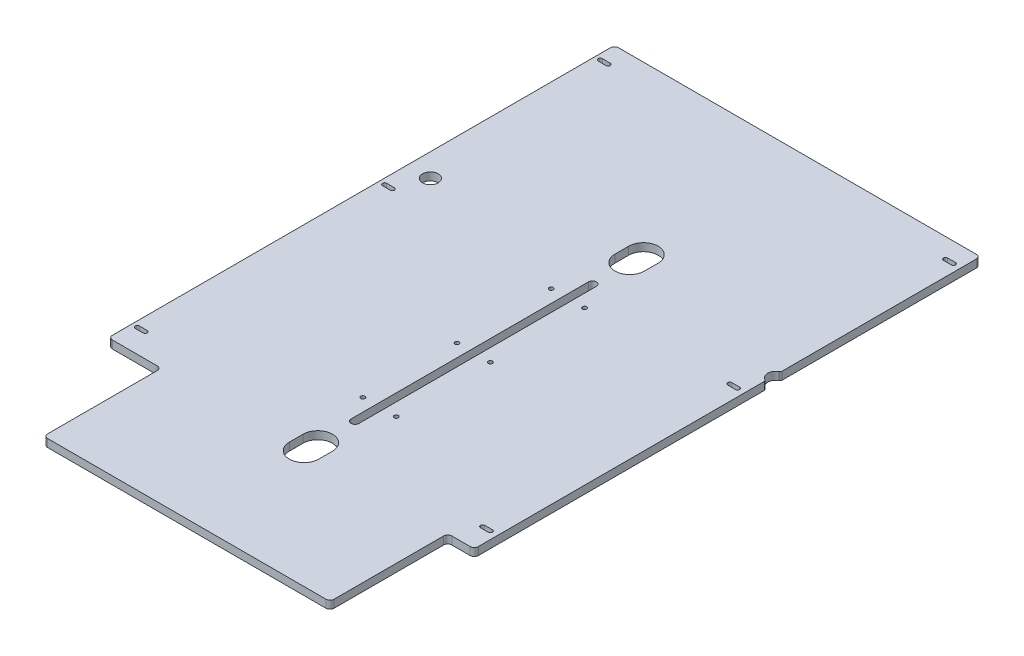
SolidWorks part; units mm, degrees
material "PE High Density"
ref_plane "Front" through (0, 0, 0) normal (0, 0, 1) x (1, 0, 0)
ref_plane "Top" through (0, 0, 0) normal (0, 1, 0) x (1, 0, 0)
ref_plane "Right" through (0, 0, 0) normal (1, 0, 0) x (0, 0, -1)
sketch "Sketch1" plane through (0, 0, 0) normal (0, 1, 0) x (1, 0, 0)
  line L0 (0, 0) -> (96.0438, 0)
  line L1 (96.0438, 0) -> (96.0438, -190.5)
  line L2 (96.0438, -190.5) -> (559.5938, -190.5)
  line L3 (559.5938, -190.5) -> (559.5938, 0)
  line L4 (559.5938, 0) -> (606.425, 0)
  line L5 (606.425, 0) -> (606.425, 819.15)
  line L6 (606.425, 819.15) -> (0, 819.15)
  line L7 (0, 819.15) -> (0, 0)
  line L8 (25.4, 0) -> (25.4, 819.15) construction
  line L9 (19.05, 38.1) -> (31.75, 38.1) construction
  line L10 (19.05, 41.4782) -> (31.75, 41.4782)
  line L11 (19.05, 34.7218) -> (31.75, 34.7218)
  line L12 (19.05, 438.15) -> (31.75, 438.15) construction
  line L13 (19.05, 441.5282) -> (31.75, 441.5282)
  line L14 (19.05, 434.7718) -> (31.75, 434.7718)
  line L15 (31.75, 787.4) -> (19.05, 787.4) construction
  line L16 (31.75, 784.0218) -> (19.05, 784.0218)
  line L17 (31.75, 790.7782) -> (19.05, 790.7782)
  line L18 (303.2125, 819.15) -> (303.2125, -190.5) construction
  line L19 (584.2, 787.4) -> (584.2, 438.15) construction
  line L20 (577.85, 787.4) -> (590.55, 787.4) construction
  line L21 (577.85, 784.0218) -> (590.55, 784.0218)
  line L22 (577.85, 790.7782) -> (590.55, 790.7782)
  line L23 (590.55, 438.15) -> (577.85, 438.15) construction
  line L24 (590.55, 441.5282) -> (577.85, 441.5282)
  line L25 (590.55, 434.7718) -> (577.85, 434.7718)
  line L26 (590.55, 38.1) -> (577.85, 38.1) construction
  line L27 (590.55, 41.4782) -> (577.85, 41.4782)
  line L28 (590.55, 34.7218) -> (577.85, 34.7218)
  line L29 (327.8187, -190.5) -> (327.8187, 819.15) construction
  line L30 (584.2, 438.15) -> (584.2, 38.1) construction
  arc A1 (19.05, 41.4782) -> (19.05, 34.7218) centre (19.05, 38.1) ccw
  arc A2 (31.75, 34.7218) -> (31.75, 41.4782) centre (31.75, 38.1) ccw
  arc A3 (19.05, 441.5282) -> (19.05, 434.7718) centre (19.05, 438.15) ccw
  arc A4 (31.75, 434.7718) -> (31.75, 441.5282) centre (31.75, 438.15) ccw
  arc A5 (31.75, 784.0218) -> (31.75, 790.7782) centre (31.75, 787.4) ccw
  arc A6 (19.05, 790.7782) -> (19.05, 784.0218) centre (19.05, 787.4) ccw
  arc A7 (577.85, 784.0218) -> (577.85, 790.7782) centre (577.85, 787.4) cw
  arc A8 (590.55, 790.7782) -> (590.55, 784.0218) centre (590.55, 787.4) cw
  arc A9 (590.55, 441.5282) -> (590.55, 434.7718) centre (590.55, 438.15) cw
  arc A10 (577.85, 434.7718) -> (577.85, 441.5282) centre (577.85, 438.15) cw
  arc A11 (590.55, 41.4782) -> (590.55, 34.7218) centre (590.55, 38.1) cw
  arc A12 (577.85, 34.7218) -> (577.85, 41.4782) centre (577.85, 38.1) cw
  point P13 (25.4, 38.1)
  point P20 (25.4, 438.15)
  point P27 (25.4, 787.4)
  point P38 (584.2, 787.4)
  point P45 (584.2, 438.15)
  point P52 (584.2, 38.1)
  dimension "D1" = 96.0438
  dimension "D2" = 46.8312
  dimension "D3" = 819.15
  dimension "D4" = 25.4
  dimension "D5" = 6.7564
  dimension "D6" = 38.1
  dimension "D7" = 12.7
  dimension "D8" = 400.05
  dimension "D9" = 349.25
  dimension "D10" = 190.5
  dimension "D11" = 463.55
  dimension "D12" = 22.225
extrude "Boss-Extrude1" add sketch "Sketch1" along normal blind 12.7
fillet "Fillet1" radius 6.604 2 edges at (96.0438, 6.35, 0) (559.5938, 6.35, 0)
fillet "Fillet2" radius 6.604 6 edges at (0, 6.35, -819.15) (606.425, 6.35, -819.15) (606.425, 6.35, 0) (559.5938, 6.35, 190.5) (0, 6.35, 0) (96.0438, 6.35, 190.5)
sketch "Sketch2" plane through (0, 12.7, 0) normal (0, 1, 0) x (1, 0, 0)
  line L1 (606.425, 6.604) -> (606.425, 812.546) construction
  line L3 (577.85, 438.15) -> (590.55, 438.15) construction
  line L4 (606.425, 505.867) -> (606.425, 461.873)
  line L5 (606.425, 483.87) -> (47.625, 483.87) construction
  line L6 (0, 812.546) -> (0, 6.604) construction
  arc A3 (600.075, 494.8685) -> (600.075, 472.8715) centre (606.425, 483.87) ccw
  arc A4 (600.075, 494.8685) -> (606.425, 505.867) centre (593.725, 505.867) ccw
  arc A5 (606.425, 461.873) -> (600.075, 472.8715) centre (593.725, 461.873) ccw
  circle A6 centre (47.625, 483.87) radius 12.7
  dimension "D1" = 25.4
  dimension "D2" = 45.72
  dimension "D3" = 47.625
extrude "Cut-Extrude1" cut sketch "Sketch2" against normal through all
sketch "Sketch4" plane through (0, 0, 0) normal (0, -1, 0) x (1, 0, 0)
  line L0 (0, -812.546) -> (0, -6.604) construction
  line L3 (327.025, -527.05) -> (327.025, -549.275) construction
  line L4 (350.8375, -527.05) -> (350.8375, -549.275)
  line L5 (303.2125, -527.05) -> (303.2125, -549.275)
  line L7 (599.821, -819.15) -> (6.604, -819.15) construction
  line L8 (327.025, 0) -> (327.025, -22.225) construction
  line L9 (350.8375, 0) -> (350.8375, -22.225)
  line L10 (303.2125, 0) -> (303.2125, -22.225)
  circle A0 centre (327.025, -538.1625) radius 28.575 construction
  arc A2 (350.8375, -527.05) -> (303.2125, -527.05) centre (327.025, -527.05) ccw
  arc A3 (303.2125, -549.275) -> (350.8375, -549.275) centre (327.025, -549.275) ccw
  arc A4 (350.8375, 0) -> (303.2125, 0) centre (327.025, 0) ccw
  arc A5 (303.2125, -22.225) -> (350.8375, -22.225) centre (327.025, -22.225) ccw
  point P8 (327.025, -11.1125)
  point P12 (327.025, -538.1625)
  dimension "D2" = 57.15
  dimension "D1" = 327.025
  dimension "D3" = 527.05
  dimension "D4" = 47.625
  dimension "D5" = 22.225
  dimension "D6" = 280.9875
extrude "Cut-Extrude3" cut sketch "Sketch4" against normal through all
sketch "Sketch5" plane through (0, 0, 0) normal (0, -1, 0) x (1, 0, 0)
  line L0 (327.025, -22.225) -> (327.025, -527.05) construction
  line L1 (327.025, -466.725) -> (327.025, -82.55) construction
  line L2 (320.675, -466.725) -> (320.675, -82.55)
  line L3 (333.375, -466.725) -> (333.375, -82.55)
  arc A0 (320.675, -466.725) -> (333.375, -466.725) centre (327.025, -466.725) ccw
  arc A1 (333.375, -82.55) -> (320.675, -82.55) centre (327.025, -82.55) ccw
  point P6 (327.025, -274.6375)
  dimension "D1" = 384.175
  dimension "D2" = 12.7
extrude "Cut-Extrude4" cut sketch "Sketch5" against normal through all
sketch "Sketch6" plane through (0, 0, 0) normal (0, -1, 0) x (1, 0, 0)
  line L0 (327.025, -82.55) -> (327.025, -466.725) construction
  line L1 (327.025, -274.6375) -> (354.0125, -274.6375) construction
  line L2 (354.0125, -122.2375) -> (354.0125, -427.0375) construction
  line L3 (300.0375, -122.2375) -> (300.0375, -427.0375) construction
  circle A0 centre (354.0125, -274.6375) radius 3.3782
  circle A1 centre (354.0125, -427.0375) radius 3.3782
  circle A2 centre (354.0125, -122.2375) radius 3.3782
  circle A3 centre (300.0375, -427.0375) radius 3.3782
  circle A4 centre (300.0375, -274.6375) radius 3.3782
  circle A5 centre (300.0375, -122.2375) radius 3.3782
  dimension "D2" = 6.7564
  dimension "D1" = 26.9875
  dimension "D3" = 152.4
extrude "Cut-Extrude5" cut sketch "Sketch6" against normal through all
sketch "Sketch7" plane through (0, 0, 0) normal (0, -1, 0) x (1, 0, 0)
  line L0 (599.821, -819.15) -> (6.604, -819.15) construction
  line L1 (6.604, 0) -> (89.4398, 0) construction
  line L2 (0, -812.546) -> (0, -6.604) construction
  line L3 (7.366, -819.15) -> (6.604, -819.15)
  line L4 (6.604, 0) -> (7.366, 0)
  line L5 (0, -812.546) -> (0, -6.604)
  line L6 (0.762, -6.604) -> (0.762, -812.546)
  line L7 (566.1978, 0) -> (599.821, 0) construction
  line L8 (606.425, -505.867) -> (606.425, -812.546) construction
  line L9 (606.425, -6.604) -> (606.425, -461.873) construction
  line L10 (566.1978, 0) -> (599.821, 0)
  line L11 (599.821, -819.15) -> (6.604, -819.15)
  line L12 (606.425, -505.867) -> (606.425, -812.546)
  line L13 (606.425, -6.604) -> (606.425, -461.873)
  line L14 (605.663, -504.5472) -> (605.663, -812.546)
  line L15 (605.663, -6.604) -> (605.663, -462.3309)
  arc A0 (0, -812.546) -> (6.604, -819.15) centre (6.604, -812.546) ccw construction
  arc A1 (6.604, 0) -> (0, -6.604) centre (6.604, -6.604) ccw construction
  arc A2 (0, -812.546) -> (6.604, -819.15) centre (6.604, -812.546) ccw
  arc A3 (6.604, 0) -> (0, -6.604) centre (6.604, -6.604) ccw
  arc A4 (7.366, 0) -> (0.762, -6.604) centre (7.366, -6.604) ccw
  arc A5 (0.762, -812.546) -> (7.366, -819.15) centre (7.366, -812.546) ccw
  arc A6 (599.821, -819.15) -> (606.425, -812.546) centre (599.821, -812.546) ccw construction
  arc A7 (606.425, -505.867) -> (600.075, -494.8685) centre (593.725, -505.867) ccw construction
  arc A8 (600.075, -472.8715) -> (600.075, -494.8685) centre (606.425, -483.87) ccw construction
  arc A9 (600.075, -472.8715) -> (606.425, -461.873) centre (593.725, -461.873) ccw construction
  arc A10 (606.425, -6.604) -> (599.821, 0) centre (599.821, -6.604) ccw construction
  arc A11 (599.821, -819.15) -> (606.425, -812.546) centre (599.821, -812.546) ccw
  arc A12 (606.425, -505.867) -> (600.075, -494.8685) centre (593.725, -505.867) ccw
  arc A13 (600.075, -472.8715) -> (600.075, -494.8685) centre (606.425, -483.87) ccw
  arc A14 (600.075, -472.8715) -> (606.425, -461.873) centre (593.725, -461.873) ccw
  arc A15 (606.425, -6.604) -> (599.821, 0) centre (599.821, -6.604) ccw
  arc A16 (605.663, -6.604) -> (599.059, 0) centre (599.059, -6.604) ccw
  arc A17 (599.059, -819.15) -> (605.663, -812.546) centre (599.059, -812.546) ccw
  arc A18 (605.663, -504.5472) -> (600.075, -494.8685) centre (594.487, -504.5472) ccw
  arc A19 (599.694, -473.1004) -> (605.663, -462.3309) centre (592.963, -462.3309) ccw
  dimension "D1" = 0.762
  dimension "D2" = 0.762
extrude "Cut-Extrude6" cut sketch "Sketch7" against normal through all contours A18 L14 A17 L11 A11 L12 A12 | A5 L6 A4 L4 A3 L5 A2 L3 | A19 A13 A14 L13 A15 L10 A16 L15
sketch "Sketch8" plane through (0, 0, 0) normal (0, -1, 0) x (1, 0, 0)
  line L0 (0.762, -6.604) -> (0.762, -812.546) construction
  line L1 (0.762, -6.604) -> (0.762, -812.546)
  line L2 (10.287, -6.604) -> (10.287, -812.546)
  line L3 (16.891, 0) -> (7.366, 0)
  line L4 (16.891, -819.15) -> (7.366, -819.15)
  line L5 (605.663, -6.604) -> (605.663, -462.3309) construction
  line L6 (605.663, -6.604) -> (605.663, -812.546)
  line L7 (602.488, -6.604) -> (602.488, -812.546)
  line L8 (595.884, -819.15) -> (599.059, -819.15)
  line L9 (595.884, 0) -> (599.059, 0)
  arc A0 (0.762, -812.546) -> (7.366, -819.15) centre (7.366, -812.546) ccw construction
  arc A1 (7.366, 0) -> (0.762, -6.604) centre (7.366, -6.604) ccw construction
  arc A2 (0.762, -812.546) -> (7.366, -819.15) centre (7.366, -812.546) ccw
  arc A3 (7.366, 0) -> (0.762, -6.604) centre (7.366, -6.604) ccw
  arc A4 (10.287, -812.546) -> (16.891, -819.15) centre (16.891, -812.546) ccw
  arc A5 (16.891, 0) -> (10.287, -6.604) centre (16.891, -6.604) ccw
  arc A6 (599.059, -819.15) -> (605.663, -812.546) centre (599.059, -812.546) ccw construction
  arc A7 (605.663, -6.604) -> (599.059, 0) centre (599.059, -6.604) ccw construction
  arc A8 (599.059, -819.15) -> (605.663, -812.546) centre (599.059, -812.546) ccw
  arc A9 (605.663, -6.604) -> (599.059, 0) centre (599.059, -6.604) ccw
  arc A10 (602.488, -6.604) -> (595.884, 0) centre (595.884, -6.604) ccw
  arc A11 (595.884, -819.15) -> (602.488, -812.546) centre (595.884, -812.546) ccw
  dimension "D2" = 9.525
  dimension "D4" = 3.175
  dimension "D1" = 2
  dimension "D3" = 2
extrude "Cut-Extrude7" cut sketch "Sketch8" against normal through all contours A11 L8 A8 L6 A9 L9 A10 L7 | L1 A2 L4 A4 L2 A5 L3 A3
fillet "Fillet3" radius 3.175 2 edges at (602.488, 6.35, -496.7442) (602.488, 6.35, -470.7311)
